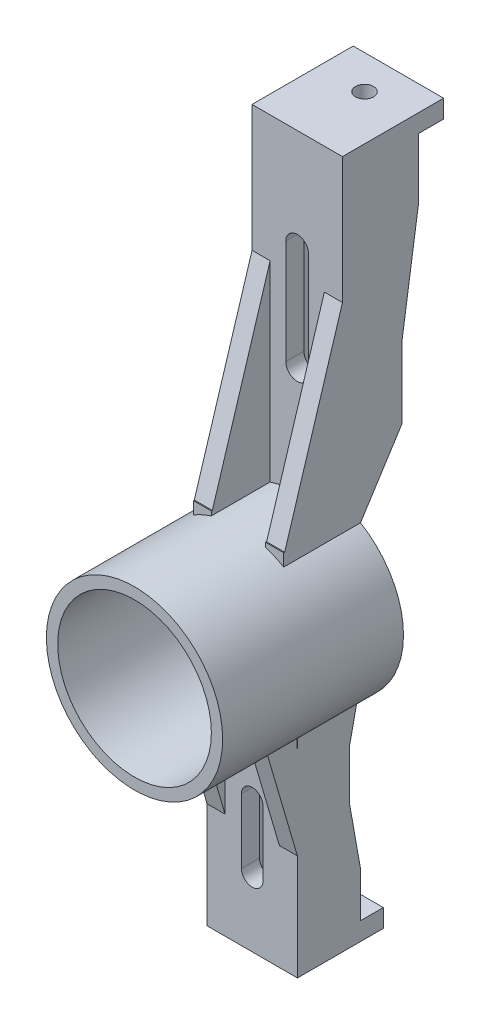
SolidWorks part; units mm, degrees
ref_plane "Front Plane" through (0, 0, 0) normal (0, 0, 1) x (1, 0, 0)
ref_plane "Top Plane" through (0, 0, 0) normal (0, 1, 0) x (1, 0, 0)
ref_plane "Right Plane" through (0, 0, 0) normal (1, 0, 0) x (0, 0, -1)
sketch "Sketch1" plane through (0, 0, 0) normal (0, 0, 1) x (1, 0, 0)
  circle A0 centre (0, 0) radius 39
  circle A1 centre (0, 0) radius 34
  dimension "D1" = 78
  dimension "D2" = 5
extrude "Boss-Extrude1" add sketch "Sketch1" along normal blind 80
sketch "Sketch3" plane through (0, 0, 0) normal (1, 0, 0) x (0, 0, -1)
  line L0 (-80, 39) -> (0, 39) construction
  line L1 (0, 39) -> (0, -39) construction
  line L2 (0, -39) -> (-80, -39) construction
  line L3 (-80, -39) -> (-80, 39) construction
  line L4 (-8, 39) -> (-8, 152.0629) construction
  line L5 (0, 39) -> (0, 162.2451) construction
  line L6 (-8, 152.0629) -> (-8, 224.6864) construction
  line L7 (0, 162.2451) -> (0, 224.6864) construction
  line L8 (-8, 39) -> (-8, 177.8)
  line L9 (-8, 177.8) -> (36.76, 177.8)
  line L10 (0, 39) -> (0, 169.8)
  line L11 (0, 169.8) -> (36.76, 169.8)
  line L12 (36.76, 169.8) -> (36.76, 177.8)
  line L13 (-8, 39) -> (0, 39)
  point P8 (-8, 39)
  point P13 (-8, 177.8)
  point P14 (0, 169.8)
  dimension "D1" = 8
  dimension "D2" = 138.8
  dimension "D3" = 130.8
  dimension "D4" = 44.76
  dimension "D5" = 36.76
extrude "Boss-Extrude2" add sketch "Sketch3" along normal mid plane 40 separate body
sketch "Sketch4" plane through (0, 0, 0) normal (1, 0, 0) x (0, 0, -1)
  line L0 (-80, 39) -> (0, 39) construction
  line L1 (0, 39) -> (0, -39) construction
  line L2 (0, -39) -> (-80, -39) construction
  line L3 (-80, -39) -> (-80, 39) construction
  line L4 (-27.91, -39) -> (-27.91, -127)
  line L5 (-19.91, -39) -> (-19.91, -119)
  line L6 (-27.91, -127) -> (10.09, -127)
  line L7 (-19.91, -119) -> (10.09, -119)
  line L8 (10.09, -127) -> (10.09, -119)
  line L9 (-27.91, -39) -> (-19.91, -39)
  point P8 (-27.91, -39)
  point P9 (-19.91, -39)
  dimension "D1" = 19.91
  dimension "D2" = 27.91
  dimension "D3" = 88
  dimension "D4" = 80
  dimension "D5" = 38
  dimension "D6" = 30
extrude "Boss-Extrude3" add sketch "Sketch4" along normal mid plane 40 separate body
sketch "Sketch6" plane through (0, 0, 19.91) normal (0, 0, -1) x (-1, 0, 0)
  line L0 (-20, -39) -> (-20, -33.4813)
  line L1 (20, -39) -> (20, -33.4813)
  line L4 (20, -119) -> (20, -39)
  line L5 (20, -39) -> (-20, -39)
  line L6 (-20, -39) -> (-20, -119)
  line L7 (-20, -119) -> (20, -119)
  line L9 (20, -39) -> (-20, -39)
  circle A1 centre (0, 0) radius 39
  arc A2 (-20, -33.4813) -> (20, -33.4813) centre (0, 0) ccw
  line M7 (20, -39) -> (-20, -39)
  dimension "D1" = 0
  dimension "D2" = 0
extrude "Boss-Extrude4" add sketch "Sketch6" against normal blind 8 contours A2 L1 M7 | A2 L0 L9
sketch "Sketch7" plane through (0, 0, 0) normal (0, 0, -1) x (-1, 0, 0)
  line L0 (-20, 39) -> (-20, 33.4813)
  line L1 (20, 39) -> (20, 33.4813)
  line L4 (20, 39) -> (20, 169.8)
  line L5 (20, 169.8) -> (-20, 169.8)
  line L6 (-20, 169.8) -> (-20, 39)
  line L7 (-20, 39) -> (20, 39)
  line L11 (-20, 39) -> (20, 39)
  circle A1 centre (0, 0) radius 39
  arc A2 (20, 33.4813) -> (-20, 33.4813) centre (0, 0) ccw
  line M9 (-20, 39) -> (20, 39)
  dimension "D1" = 0
  dimension "D2" = 0
extrude "Boss-Extrude5" add sketch "Sketch7" against normal blind 8 contours A2 L0 M9 | A2 L1 L11
sketch "Sketch9" plane through (0, 0, 80) normal (0, 0, 1) x (1, 0, 0)
  circle A0 centre (0, 0) radius 107.5
  dimension "D1" = 215
sketch "Sketch10" plane through (0, 0, 0) normal (1, 0, 0) x (0, 0, -1)
  line L0 (-80, 39) -> (-80, -39) construction
  line L1 (-80, -39) -> (0, -39) construction
  line L2 (0, -39) -> (0, 39) construction
  line L3 (0, 33.4813) -> (0, 169.8) construction
  line L4 (0, 39) -> (-80, 39) construction
  line L5 (-80, 0) -> (-57, 0) construction
  line L6 (-57, 72.5) -> (-57, -72.5)
  point P14 (-57, 0)
  dimension "D1" = 23
  dimension "D2" = 145
sketch "Sketch11" plane through (0, 0, 0) normal (0, 0, -1) x (-1, 0, 0)
  line L0 (-159.5823, 0) -> (159.5823, 0)
  point P5 (0, 0)
sketch "Sketch12" plane through (0, 0, 0) normal (0, 0, -1) x (-1, 0, 0)
  line L0 (0, 169.8) -> (0, -119) construction
  line L1 (-20, 169.8) -> (20, 169.8) construction
  line L2 (-20, -119) -> (20, -119) construction
  line L3 (0, 132.9337) -> (0, 86.7104) construction
  line L4 (5.0599, 132.9337) -> (5.0599, 86.7104)
  line L5 (-5.0599, 132.9337) -> (-5.0599, 86.7104)
  line L6 (0, -68.7373) -> (0, -97.4445) construction
  line L7 (4.7564, -68.7373) -> (4.7564, -97.4445)
  line L8 (-4.7564, -68.7373) -> (-4.7564, -97.4445)
  arc A0 (5.0599, 132.9337) -> (-5.0599, 132.9337) centre (0, 132.9337) ccw
  arc A1 (-5.0599, 86.7104) -> (5.0599, 86.7104) centre (0, 86.7104) ccw
  arc A2 (4.7564, -68.7373) -> (-4.7564, -68.7373) centre (0, -68.7373) ccw
  arc A3 (-4.7564, -97.4445) -> (4.7564, -97.4445) centre (0, -97.4445) ccw
  point P8 (0, 109.822)
  point P15 (0, -83.0909)
extrude "Cut-Extrude1" cut sketch "Sketch12" against normal blind 73
sketch "Sketch13" plane through (0, 177.8, 0) normal (0, 1, 0) x (1, 0, 0)
  line L0 (0, 36.76) -> (0, 21.76) construction
  line L1 (20, 36.76) -> (-20, 36.76) construction
  circle A0 centre (0, 21.76) radius 4
  dimension "D2" = 8
  dimension "D1" = 15
extrude "Cut-Extrude2" cut sketch "Sketch13" against normal blind 24
sketch "Sketch14" plane through (0, -127, 0) normal (0, -1, 0) x (1, 0, 0)
  line L0 (0, -10.09) -> (0, 4.91) construction
  line L1 (20, -10.09) -> (-20, -10.09) construction
  circle A0 centre (0, 4.91) radius 4
  dimension "D2" = 8
  dimension "D1" = 15
extrude "Cut-Extrude3" cut sketch "Sketch14" against normal blind 24
sketch "Sketch15" plane through (20, 0, 0) normal (1, 0, 0) x (0, 0, -1)
  line L0 (10.09, -119) -> (-19.91, -119) construction
  line L1 (0, -119) -> (0, -99.0869)
  line L2 (0, -99.0869) -> (-4.91, -71.4646)
  line L3 (-4.91, -71.4646) -> (-4.91, -49.8147)
  line L4 (-4.91, -49.8147) -> (-1.413, -33.6347)
  line L5 (-1.413, -33.6347) -> (-19.91, -33.4813)
  line L6 (-19.91, -119) -> (-19.91, -33.4813) construction
  line L7 (-19.91, -39) -> (-19.91, -33.4813) construction
  line L8 (-19.91, -33.4813) -> (-19.91, -119)
  line L9 (-19.91, -119) -> (0, -119)
extrude "Boss-Extrude6" add sketch "Sketch15" against normal blind 8
sketch "Sketch16" plane through (-20, 0, 0) normal (-1, 0, 0) x (0, 0, 1)
  line L0 (0, -119) -> (0, -99.0869)
  line L1 (0, -99.0869) -> (4.91, -71.4646)
  line L2 (4.91, -71.4646) -> (4.91, -49.8147)
  line L3 (4.91, -49.8147) -> (1.3799, -33.4813)
  line L4 (4.91, -49.8147) -> (2.1637, -37.108) construction
  line L5 (1.3799, -33.4813) -> (19.91, -33.4813)
  line L6 (19.91, -33.4813) -> (19.91, -39) construction
  line L7 (19.91, -119) -> (0, -119)
  line L8 (19.91, -33.4813) -> (19.91, -119)
  line L9 (27.91, -33.4813) -> (19.91, -33.4813) construction
extrude "Boss-Extrude7" add sketch "Sketch16" against normal blind 8
sketch "Sketch17" plane through (20, 0, 0) normal (1, 0, 0) x (0, 0, -1)
  line L0 (25.76, 169.8) -> (25.76, 143.643)
  line L1 (25.76, 143.643) -> (18.38, 94.2017)
  line L2 (18.38, 94.2017) -> (18.38, 62.3041)
  line L3 (18.38, 62.3041) -> (0, 33.4813)
  line L4 (0, 33.4813) -> (0, 169.8) construction
  line L5 (0, 33.4813) -> (0, 169.8)
  line L6 (0, 169.8) -> (25.76, 169.8)
extrude "Boss-Extrude8" add sketch "Sketch17" against normal blind 8
sketch "Sketch23" plane through (20, 0, 0) normal (1, 0, 0) x (0, 0, -1)
  line L4 (-8, 121.8913) -> (-33.5648, 39)
  line L5 (-8, 177.8) -> (-8, 33.4813) construction
  line L6 (-40, -39) -> (-27.91, -80.2407)
  line L7 (-27.91, -33.4813) -> (-27.91, -127) construction
  line L8 (-8, 121.8913) -> (-8, 39)
  line L9 (-8, 39) -> (-33.5648, 39)
  line L10 (-40, -39) -> (-27.91, -39)
  line L11 (-27.91, -39) -> (-27.91, -80.2407)
extrude "Boss-Extrude14" add sketch "Sketch23" against normal blind 8
sketch "Sketch24" plane through (-20, 0, 0) normal (-1, 0, 0) x (0, 0, 1)
  line L6 (0, 169.8) -> (-25.76, 169.8)
  line L7 (-25.76, 169.8) -> (-25.76, 143.643)
  line L8 (-25.76, 143.643) -> (-18.38, 94.2017)
  line L9 (-18.38, 94.2017) -> (-18.38, 62.3041)
  line L10 (-18.38, 62.3041) -> (0, 33.4813)
  line L11 (0, 33.4813) -> (0, 169.8)
  line L12 (0, 169.8) -> (-25.76, 169.8)
  line L13 (-25.76, 169.8) -> (-25.76, 143.643)
  line L14 (-25.76, 143.643) -> (-18.38, 94.2017)
  line L15 (-18.38, 94.2017) -> (-18.38, 62.3041)
  line L16 (-18.38, 62.3041) -> (0, 33.4813)
  line L17 (0, 33.4813) -> (0, 169.8)
  dimension "D1" = 0
extrude "Boss-Extrude15" add sketch "Sketch24" against normal blind 8
sketch "Sketch25" plane through (-20, 0, 0) normal (-1, 0, 0) x (0, 0, 1)
  line L3 (8, 39) -> (33.5648, 39)
  line L4 (33.5648, 39) -> (8, 121.8913)
  line L5 (8, 121.8913) -> (8, 39)
  line L6 (8, 39) -> (33.5648, 39)
  line L7 (33.5648, 39) -> (8, 121.8913)
  line L8 (8, 121.8913) -> (8, 39)
  dimension "D1" = 0
extrude "Boss-Extrude16" add sketch "Sketch25" against normal blind 8
sketch "Sketch26" plane through (-20, 0, 0) normal (-1, 0, 0) x (0, 0, 1)
  line L3 (27.91, -39) -> (27.91, -80.2407)
  line L4 (27.91, -80.2407) -> (40, -39)
  line L5 (40, -39) -> (27.91, -39)
  line L6 (27.91, -39) -> (27.91, -80.2407)
  line L7 (27.91, -80.2407) -> (40, -39)
  line L8 (40, -39) -> (27.91, -39)
  dimension "D1" = 0
extrude "Boss-Extrude17" add sketch "Sketch26" against normal blind 8
ref_plane "Plane1" through (0, 0, 8) normal (0, 0, 1) x (1, 0, 0)
sketch "Sketch28" plane through (0, 0, 8) normal (0, 0, 1) x (1, 0, 0)
  line L0 (-12, 39) -> (-12, 37.108)
  line L1 (12, 39) -> (12, 37.108)
  line L11 (-20, 177.8) -> (-20, 121.8913)
  line L12 (-20, 121.8913) -> (-12, 121.8913)
  line L13 (-12, 121.8913) -> (-12, 39)
  line L14 (-12, 39) -> (-20, 39)
  line L15 (-20, 39) -> (-20, 33.4813)
  line L16 (20, 33.4813) -> (20, 39)
  line L17 (20, 39) -> (12, 39)
  line L18 (12, 39) -> (12, 121.8913)
  line L19 (12, 121.8913) -> (20, 121.8913)
  line L20 (20, 121.8913) -> (20, 177.8)
  line L21 (20, 177.8) -> (-20, 177.8)
  line L25 (-12, 39) -> (-20, 39)
  line L26 (-20, 39) -> (-20, 33.4813)
  line L27 (20, 33.4813) -> (20, 39)
  line L28 (20, 39) -> (12, 39)
  line L32 (20, 177.8) -> (-20, 177.8)
  arc A0 (-12, 37.108) -> (-20, 33.4813) centre (0, 0) ccw
  arc A1 (20, 33.4813) -> (-20, 33.4813) centre (0, 0) ccw
  arc A2 (20, 33.4813) -> (12, 37.108) centre (0, 0) ccw
  dimension "D1" = 0
extrude "Boss-Extrude18" add sketch "Sketch28" along normal blind 26 contours A0 L0 L25 L26 | A2 L27 L28 L1
ref_plane "Plane2" through (0, 0, 28) normal (0, 0, 1) x (1, 0, 0)
sketch "Sketch29" plane through (0, 0, 28) normal (0, 0, 1) x (1, 0, 0)
  line L0 (-12, -39) -> (-12, -37.108)
  line L1 (12, -39) -> (12, -37.108)
  line L11 (-20, -33.4813) -> (-20, -39)
  line L12 (-20, -39) -> (-12, -39)
  line L13 (-12, -39) -> (-12, -80.2407)
  line L14 (-12, -80.2407) -> (-20, -80.2407)
  line L15 (-20, -80.2407) -> (-20, -127)
  line L16 (-20, -127) -> (20, -127)
  line L17 (20, -127) -> (20, -80.2407)
  line L18 (20, -80.2407) -> (12, -80.2407)
  line L19 (12, -80.2407) -> (12, -39)
  line L20 (12, -39) -> (20, -39)
  line L21 (20, -39) -> (20, -33.4813)
  line L22 (-20, -33.4813) -> (-20, -39)
  line L23 (-20, -39) -> (-12, -39)
  line L31 (12, -39) -> (20, -39)
  line L32 (20, -39) -> (20, -33.4813)
  arc A0 (12, -37.108) -> (20, -33.4813) centre (0, 0) ccw
  arc A1 (-20, -33.4813) -> (20, -33.4813) centre (0, 0) ccw
  arc A2 (-20, -33.4813) -> (-12, -37.108) centre (0, 0) ccw
  dimension "D1" = 0
extrude "Boss-Extrude19" add sketch "Sketch29" along normal up to surface (13.6178 mm away)
